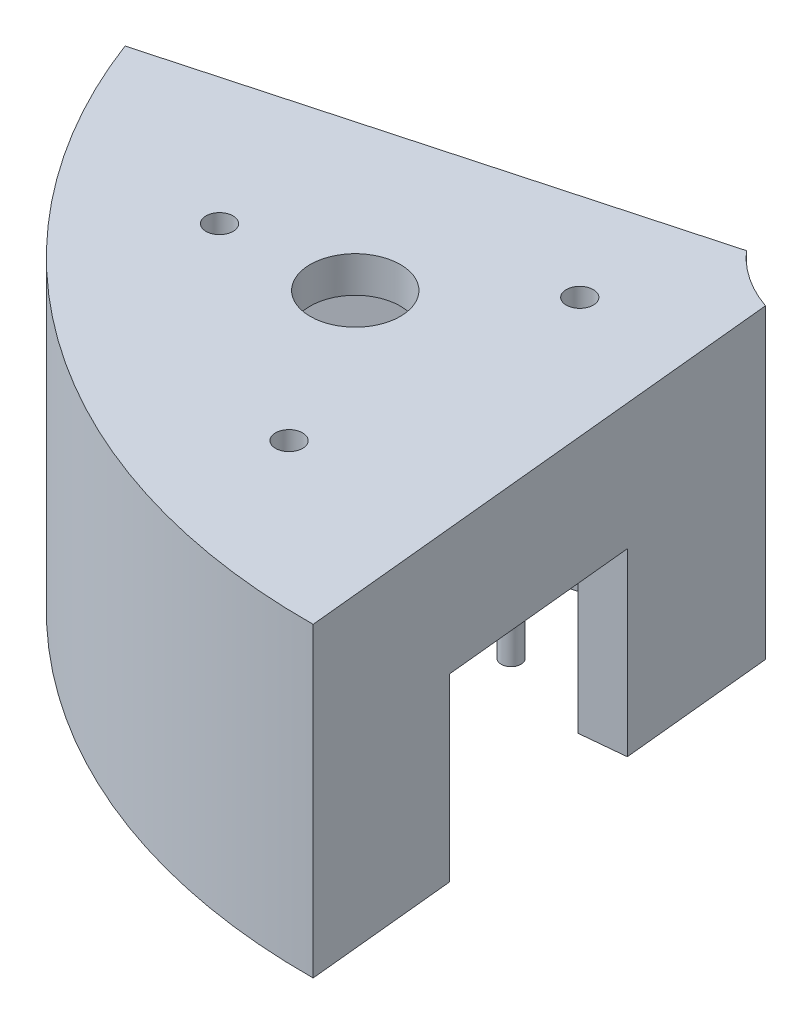
SolidWorks part; units mm, degrees
ref_plane "Front" through (0, 0, 0) normal (0, 0, 1) x (1, 0, 0)
ref_plane "Top" through (0, 0, 0) normal (0, 1, 0) x (1, 0, 0)
ref_plane "Right" through (0, 0, 0) normal (1, 0, 0) x (0, 0, -1)
other "Center of Mass"
sketch "Sketch1" plane through (0, 0, 0) normal (0, 1, 0) x (1, 0, 0)
  line L7 (-76.0816, -29.4666) -> (-21.9237, -14.6501)
  line L9 (-10.0441, -74.6224) -> (-15.5602, -18.8948)
  arc A3 (-21.9237, -14.6501) -> (-15.5602, -18.8948) centre (-10.6934, -4.7062) ccw
  arc A4 (-76.0816, -29.4666) -> (-10.0441, -74.6224) centre (-10.6934, -4.7062) ccw
  dimension "D1" = 15
  dimension "D2" = 56
  dimension "D3" = 80
extrude "Boss-Extrude1" add sketch "Sketch1" along normal blind 34
sketch "Sketch2" plane through (0, 0, 0) normal (0, -1, 0) x (1, 0, 0)
  line L0 (-15.616, 70.2424) -> (-20.1104, 23.6853)
  line L1 (-24.1919, 20.4544) -> (-69.7881, 33.0471)
  arc A0 (-15.616, 70.2424) -> (-69.7881, 33.0471) centre (-7.7156, 0.6896) ccw
  arc A1 (-20.1104, 23.6853) -> (-24.1919, 20.4544) centre (-12.1841, 9.4788) ccw
  arc A5 (-10.0441, 74.6224) -> (-76.0816, 29.4666) centre (-10.6934, 4.7062) ccw construction
  arc A6 (-15.5602, 18.8948) -> (-21.9237, 14.6501) centre (-10.6934, 4.7062) ccw construction
  dimension "D3" = 5
  dimension "D1" = 5
  dimension "D7" = 6.6071
  dimension "D2" = 70
extrude "Cut-Extrude1" cut sketch "Sketch2" against normal blind 30
sketch "Sketch3" plane through (0, 30, 0) normal (0, -1, 0) x (1, 0, 0)
  line L0 (-21.9237, 14.6501) -> (-76.0816, 29.4666) construction
  line L1 (-53.7601, 41.2992) -> (-26.6787, 28.392)
  line L2 (-26.6787, 28.392) -> (-29.0414, 58.2988)
  line L3 (-29.0414, 58.2988) -> (-53.7601, 41.2992)
  line L4 (-10.0441, 74.6224) -> (-15.5602, 18.8948) construction
  circle A0 centre (-36.4934, 42.6633) radius 8.6603 construction
  circle A1 centre (-26.6787, 28.392) radius 1.5
  circle A2 centre (-53.7601, 41.2992) radius 1.5
  circle A3 centre (-29.0414, 58.2988) radius 1.5
  circle A4 centre (-39.8044, 40.1866) radius 5
  point P14 (0, 0)
  dimension "D1" = 3
  dimension "D2" = 3
  dimension "D3" = 3
  dimension "D9" = 5
  dimension "D10" = 14
  dimension "D11" = 10
  dimension "D4" = 30
  dimension "D5" = 12
  dimension "D6" = 12
  dimension "D7" = 169.83
  dimension "D8" = 169.818
extrude "Cut-Extrude2" cut sketch "Sketch3" against normal blind 5
sketch "Sketch4" plane through (-22.1901, 0, 2.1421) normal (-0.9954, 0, 0.0961) x (0.0961, 0, 0.9954)
  line L0 (73.312, 0) -> (17.3122, 0) construction
  line L1 (56.4168, 20) -> (34.4168, 20)
  line L2 (56.4168, 20) -> (56.4168, 0)
  line L3 (56.4168, 0) -> (34.4168, 0)
  line L4 (34.4168, 20) -> (34.4168, 0)
  line L7 (68.4168, 30) -> (68.4168, 0) construction
  dimension "D1" = 20
  dimension "D2" = 22
  dimension "D3" = 0
  dimension "D4" = 12
extrude "Cut-Extrude3" cut sketch "Sketch4" against normal blind 6
sketch "Sketch5" plane through (2.2022, 0, 8.0497) normal (-0.2639, 0, -0.9646) x (-0.9646, 0, 0.2639)
  line L0 (25.0125, 0) -> (81.1606, 0) construction
  line L1 (42.035, 0) -> (64.035, 0)
  line L2 (42.035, 0) -> (42.035, 20)
  line L3 (42.035, 20) -> (64.035, 20)
  line L4 (64.035, 0) -> (64.035, 20)
  line L6 (76.035, 30) -> (76.035, 0) construction
  dimension "D1" = 20
  dimension "D2" = 22
  dimension "D3" = 0
  dimension "D4" = 12
extrude "Cut-Extrude4" cut sketch "Sketch5" against normal blind 6
sketch "Sketch10" plane through (0, 30, 0) normal (0, -1, 0) x (1, 0, 0)
  line L0 (-18.883, 36.3997) -> (-16.7691, 58.2979)
  line L5 (-18.883, 36.3997) -> (-25.8506, 37.0723)
  line L6 (-16.7691, 58.2979) -> (-23.7367, 58.9705)
  line L7 (-25.8506, 37.0723) -> (-23.7367, 58.9705)
  line L8 (-37.0149, 23.9958) -> (-58.2211, 29.8526)
  line L9 (-37.0149, 23.9958) -> (-35.1514, 30.7432)
  line L10 (-58.2211, 29.8526) -> (-56.3576, 36.6)
  line L11 (-35.1514, 30.7432) -> (-56.3576, 36.6)
  dimension "D1" = 7
  dimension "D2" = 7
extrude "Boss-Extrude2" add sketch "Sketch10" along normal blind 10
sketch "Sketch13" plane through (0, 20, 0) normal (0, -1, 0) x (1, 0, 0)
  line L0 (-35.1514, 30.7432) -> (-56.3576, 36.6) construction
  line L1 (-56.3576, 36.6) -> (-58.2211, 29.8526) construction
  line L2 (-16.7691, 58.2979) -> (-23.7367, 58.9705) construction
  line L3 (-23.7367, 58.9705) -> (-25.8506, 37.0723) construction
  circle A0 centre (-51.9612, 29.6798) radius 1.1
  circle A1 centre (-42.804, 27.1508) radius 1.1
  circle A2 centre (-18.8463, 52.3902) radius 1.1
  circle A3 centre (-19.7592, 42.9341) radius 1.1
  dimension "D5" = 2.2
  dimension "D6" = 2.2
  dimension "D7" = 2.2
  dimension "D8" = 2.2
  dimension "D12" = 9.5
  dimension "D1" = 5.5
  dimension "D2" = 6.08
  dimension "D3" = 9.5
  dimension "D4" = 5.5
  dimension "D9" = 6.08
  dimension "D10" = 5.5
  dimension "D11" = 5.5
extrude "Boss-Extrude3" add sketch "Sketch13" along normal blind 10
